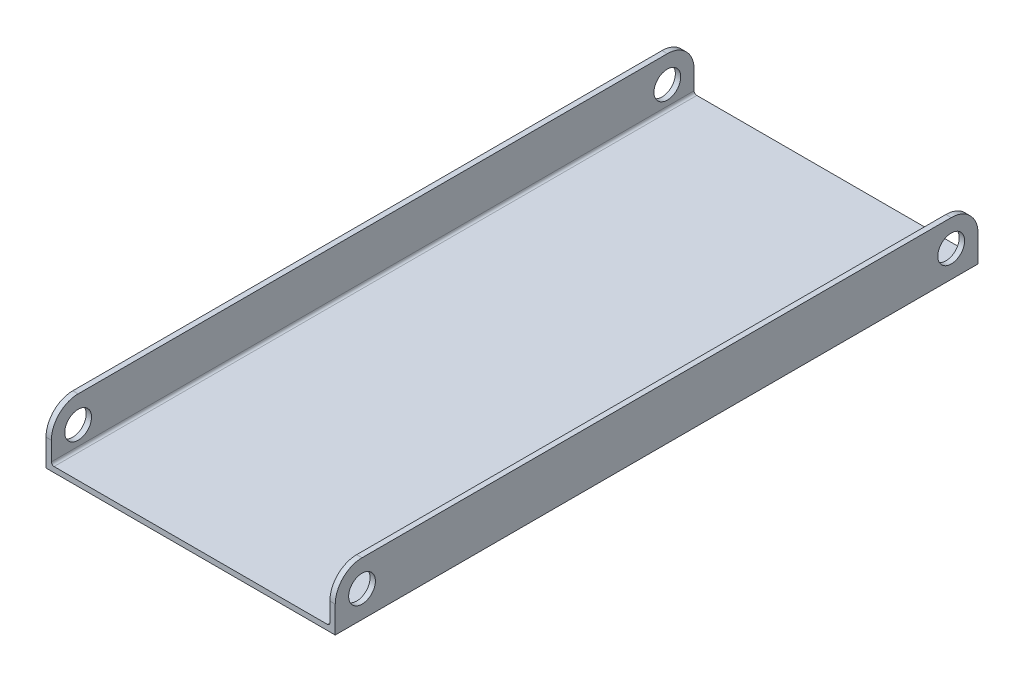
SolidWorks part; units mm, degrees
material "AISI 1020"
ref_plane "Front Plane" through (0, 0, 0) normal (0, 0, 1) x (1, 0, 0)
ref_plane "Top Plane" through (0, 0, 0) normal (0, 1, 0) x (1, 0, 0)
ref_plane "Right Plane" through (0, 0, 0) normal (1, 0, 0) x (0, 0, -1)
sketch "Sketch1" plane through (0, 0, 0) normal (0, 0, 1) x (1, 0, 0)
  line L0 (0, 0) -> (-68.58, 0)
  line L1 (-68.58, 0) -> (-68.58, 12.7)
  line L2 (-68.58, 12.7) -> (-67.31, 12.7)
  line L3 (-67.31, 12.7) -> (-67.31, 1.27)
  line L4 (-67.31, 1.27) -> (-1.27, 1.27)
  line L5 (-1.27, 1.27) -> (-1.27, 12.7)
  line L6 (-1.27, 12.7) -> (0, 12.7)
  line L7 (0, 12.7) -> (0, 0)
  line L8 (-34.29, 0) -> (-34.29, 32.031) construction
  dimension "D1" = 68.58
  dimension "D2" = 66.04
  dimension "D3" = 1.27
  dimension "D4" = 12.7
extrude "Boss-Extrude1" add sketch "Sketch1" against normal blind 152.4
fillet "Fillet1" radius 0.635 2 edges at (-1.27, 1.27, -76.2) (-67.31, 1.27, -76.2)
fillet "Fillet2" radius 6.35 4 edges at (-67.945, 12.7, -152.4) (-0.635, 12.7, -152.4) (-0.635, 12.7, 0) (-67.945, 12.7, 0)
sketch "Sketch3" plane through (0, 0, 0) normal (1, 0, 0) x (0, 0, -1)
  circle A0 centre (6.35, 6.35) radius 3.175
  circle A1 centre (146.05, 6.35) radius 3.175
  dimension "D1" = 6.35
extrude "Cut-Extrude1" cut sketch "Sketch3" against normal blind 152.4
